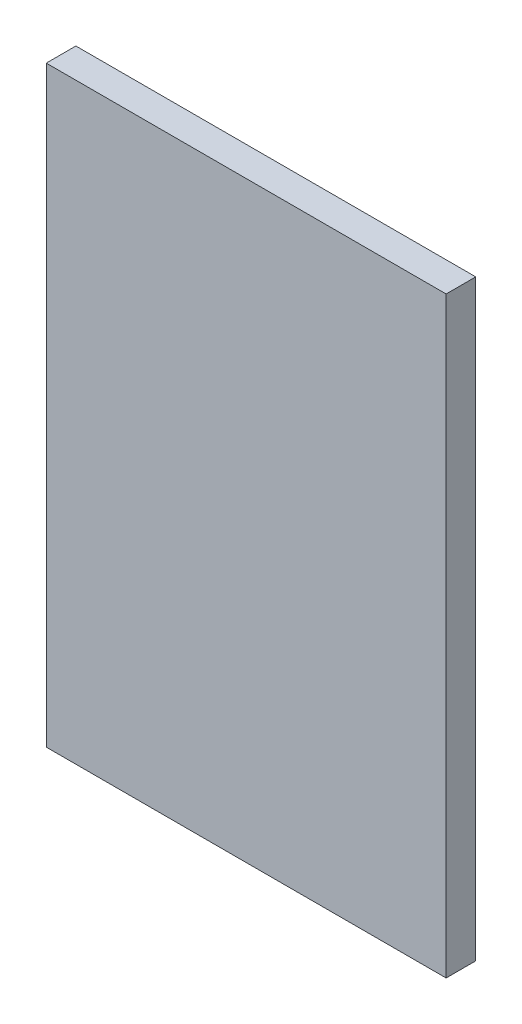
SolidWorks part; units mm, degrees
ref_plane "Alzado" through (0, 0, 0) normal (0, 0, 1) x (1, 0, 0)
ref_plane "Planta" through (0, 0, 0) normal (0, 1, 0) x (1, 0, 0)
ref_plane "Vista lateral" through (0, 0, 0) normal (1, 0, 0) x (0, 0, -1)
ref_plane "Plano_CajaSujetadoraNorte" through (0, 630, 0) normal (0, 1, 0) x (1, 0, 0)
sketch "SkCajaSujetadoraNorte" plane through (0, 630, 0) normal (0, 1, 0) x (1, 0, 0)
  line L1 (-135, -155) -> (135, -155)
  line L2 (-135, -155) -> (-135, -135)
  line L3 (-135, -135) -> (135, -135)
  line L4 (135, -155) -> (135, -135)
extrude "CajaSujetadoraNorte" add sketch "SkCajaSujetadoraNorte" along normal blind 400 separate body
